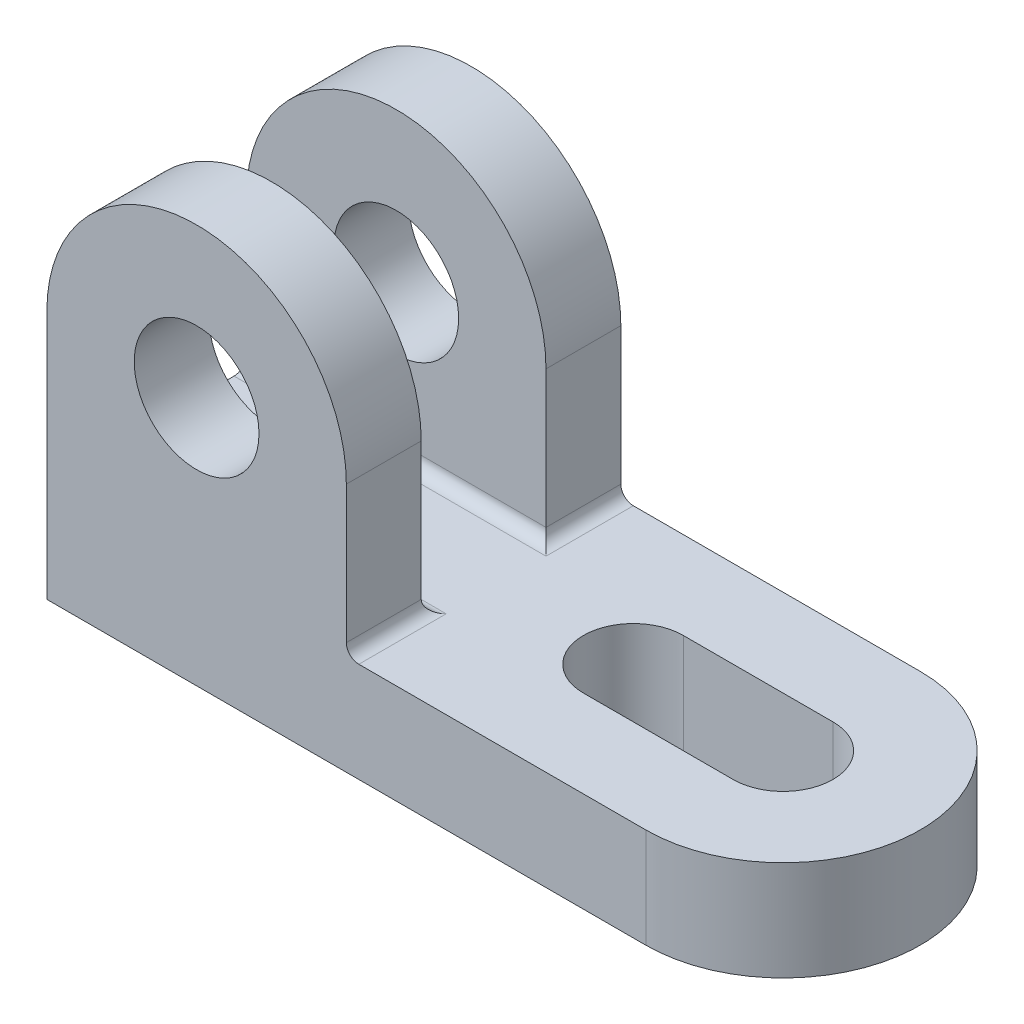
SolidWorks part; units mm, degrees
ref_plane "Front Plane" through (0, 0, 0) normal (0, 0, 1) x (1, 0, 0)
ref_plane "Top Plane" through (0, 0, 0) normal (0, 1, 0) x (1, 0, 0)
ref_plane "Right Plane" through (0, 0, 0) normal (1, 0, 0) x (0, 0, -1)
sketch "Sketch2" plane through (0, 0, 0) normal (0, 1, 0) x (1, 0, 0)
  line L1 (-59, 22) -> (59, 22)
  line L2 (-59, 22) -> (-59, -22)
  line L3 (-59, -22) -> (59, -22)
  line L4 (59, 22) -> (59, -22)
  line L5 (-59, 22) -> (59, -22) construction
  line L6 (-59, -22) -> (59, 22) construction
  circle A0 centre (37, 0) radius 22
  point P0 (0, 0)
  point P6 (0, 0)
  dimension "D1" = 118
  dimension "D2" = 44
extrude "Boss-Extrude2" add sketch "Sketch2" along normal blind 16 contours A0 L1 L2 L3 | A0
sketch "Sketch3" plane through (0, 16, 0) normal (0, 1, 0) x (1, 0, 0)
  line L0 (37, 0) -> (13, 0) construction
  line L1 (37, -8) -> (13, -8)
  line L2 (37, 8) -> (13, 8)
  arc A0 (37, -8) -> (37, 8) centre (37, 0) ccw
  arc A1 (13, 8) -> (13, -8) centre (13, 0) ccw
  point P4 (25, 0)
  dimension "D2" = 8
  dimension "D1" = 24
extrude "Cut-Extrude1" cut sketch "Sketch3" against normal blind 16
sketch "Sketch4" plane through (0, 0, 22) normal (0, 0, 1) x (1, 0, 0)
  line L0 (-59, 0) -> (37, 0) construction
  line L1 (-59, 16) -> (-11, 16)
  line L2 (-59, 16) -> (-59, 40)
  line L3 (-59, 40) -> (-11, 40)
  line L4 (-11, 16) -> (-11, 40)
  circle A0 centre (-35, 40) radius 24
  circle A1 centre (-35, 40) radius 10
  line M5 (37, 16) -> (-59, 16)
  dimension "D3" = 20
  dimension "D1" = 40
  dimension "D2" = 48
extrude "Boss-Extrude3" add sketch "Sketch4" against normal blind 12 contours A0 L4 M5 | A0 L2 L1 | A1 L3 A0 | A1 L3 A0
mirror "Mirror1" about plane through (0, 0, 0) normal (0, 0, 1) of "Boss-Extrude3"
fillet "Fillet1" radius 2 4 edges at (-35, 16, 10) (-11, 16, 16) (-11, 16, -16) (-35, 16, -10)
